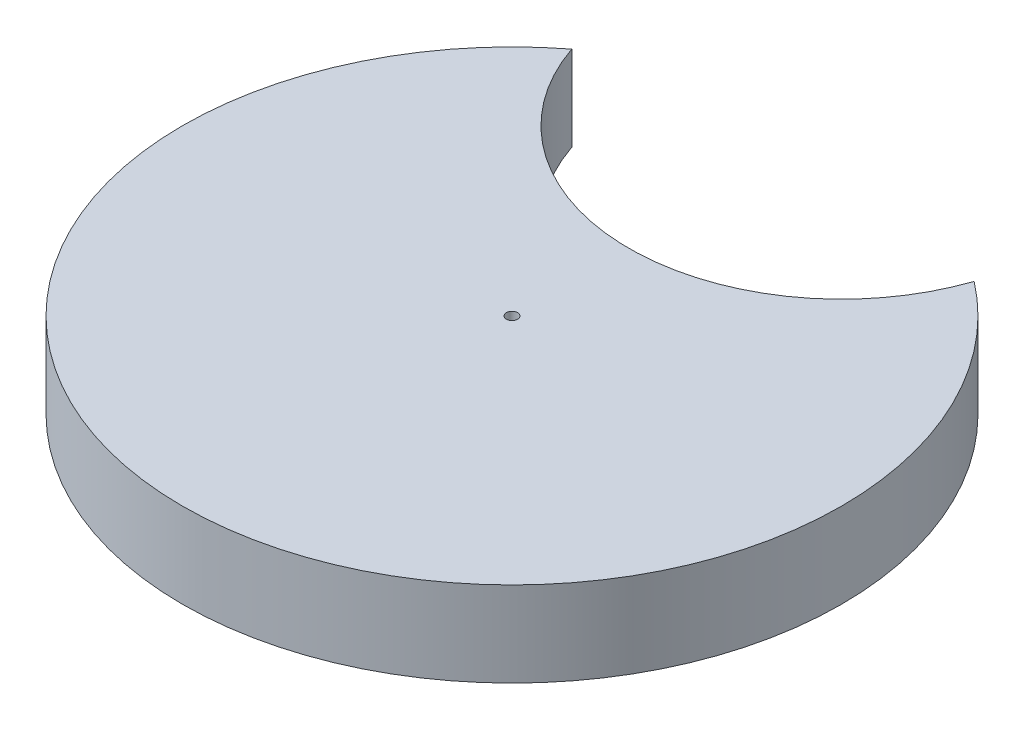
SolidWorks part; units mm, degrees
ref_plane "Front Plane" through (0, 0, 0) normal (0, 0, 1) x (1, 0, 0)
ref_plane "Top Plane" through (0, 0, 0) normal (0, 1, 0) x (1, 0, 0)
ref_plane "Right Plane" through (0, 0, 0) normal (1, 0, 0) x (0, 0, -1)
sketch "Sketch1" plane through (0, 0, 0) normal (0, 1, 0) x (1, 0, 0)
  line L0 (0, 100) -> (0, 95.6362) construction
  line L1 (-100, 0) -> (-95.6362, 0) construction
  line L2 (-20.6362, 0) -> (0, 0) construction
  line L4 (0, 20.6362) -> (0, 0) construction
  line L6 (0, 20.6362) -> (0, 0) construction
  line L7 (95.6362, 0) -> (100, 0) construction
  line L8 (-20.6362, 0) -> (0, 0) construction
  line L9 (0, -95.6362) -> (0, -100) construction
  arc A0 (0, -100) -> (100, 0) centre (0, 0) ccw
  arc A1 (-35.4961, 46.0418) -> (35.4961, 46.0418) centre (0, 58.1362) ccw
  arc A5 (-35.4961, 46.0418) -> (35.4961, 46.0418) centre (0, 0) ccw
  dimension "D1" = 200
extrude "Boss-Extrude1" add sketch "Sketch1" along normal blind 15 contours A1 A5
sketch "Sketch2" plane through (0, 0, 0) normal (0, -1, 0) x (1, 0, 0)
  line L0 (0, 0) -> (47.6746, 0) construction
  line L1 (4.899, 1) -> (7.449, 1)
  line L2 (7.449, 1) -> (7.449, 0)
  line L3 (7.449, 0) -> (7.449, -1)
  line L4 (7.449, -1) -> (4.899, -1)
  circle A0 centre (0, 0) radius 5
  dimension "D1" = 10
  dimension "D2" = 2.55
  dimension "D3" = 1
extrude "Cut-Extrude1" cut sketch "Sketch2" against normal blind 10
sketch "Sketch3" plane through (0, 15, 0) normal (0, 1, 0) x (1, 0, 0)
  circle A0 centre (0, 0) radius 1
  dimension "D1" = 2
extrude "Cut-Extrude2" cut sketch "Sketch3" against normal blind 10
